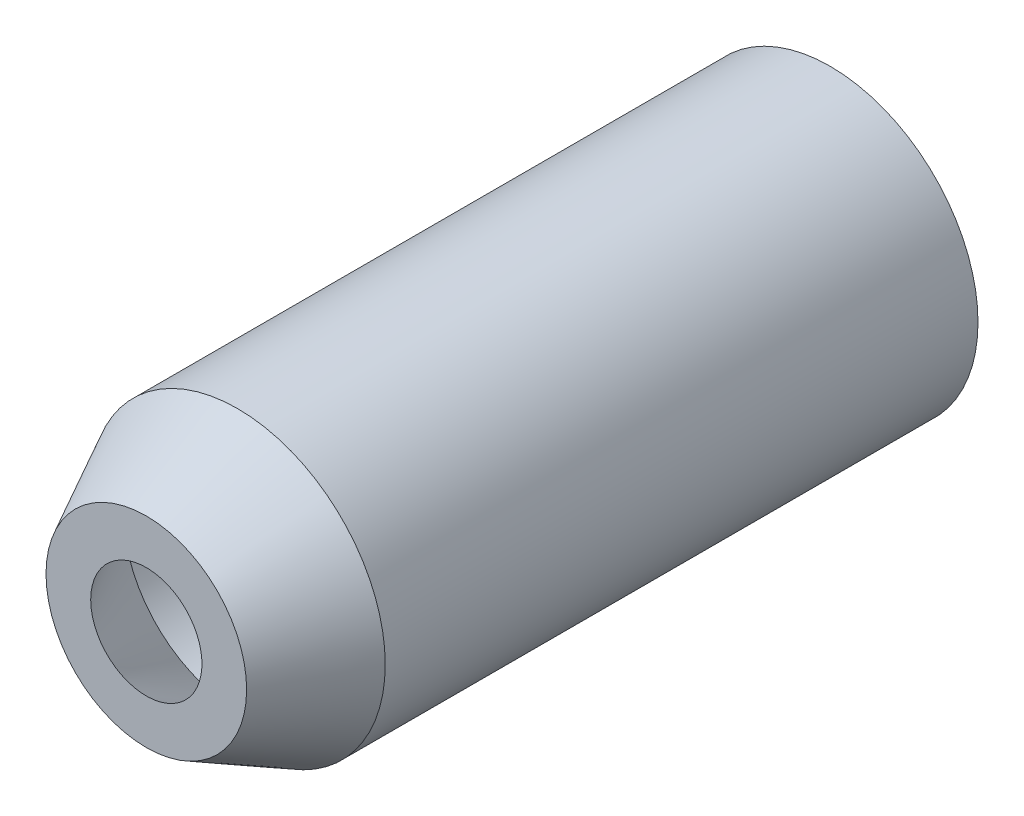
SolidWorks part; units mm, degrees
ref_plane "Front Plane" through (0, 0, 0) normal (0, 0, 1) x (1, 0, 0)
ref_plane "Top Plane" through (0, 0, 0) normal (0, 1, 0) x (1, 0, 0)
ref_plane "Right Plane" through (0, 0, 0) normal (1, 0, 0) x (0, 0, -1)
sketch "Sketch1" plane through (0, 0, 0) normal (0, 0, 1) x (1, 0, 0)
  circle A0 centre (0, 0) radius 25
  circle A1 centre (0, 0) radius 32.4
  dimension "D1" = 50
  dimension "D2" = 64.8
extrude "Boss-Extrude1" add sketch "Sketch1" along normal blind 130
sketch "Sketch6" plane through (0, 0, 0) normal (0, 1, 0) x (1, 0, 0)
  line L0 (0, 1366.1432) -> (0, -633.8568) construction
  dimension "D1" = 2000
sketch "Sketch8" plane through (0, 0, 0) normal (1, 0, 0) x (0, 0, -1)
  line L0 (-130, 32.4) -> (-150, 22)
  line L1 (-130, 25) -> (-150, 12.2)
  line L2 (1366.1432, 0) -> (-633.8568, 0) construction
  line L3 (-130, 25) -> (-130, -25) construction
  line L5 (-150, 12.2) -> (-150, 22)
  line L6 (-130, 25) -> (-130, 32.4)
  dimension "D1" = 12.2
  dimension "D2" = 22
  dimension "D3" = 20
revolve "Revolve1" add sketch "Sketch8" angle 360 about L0
